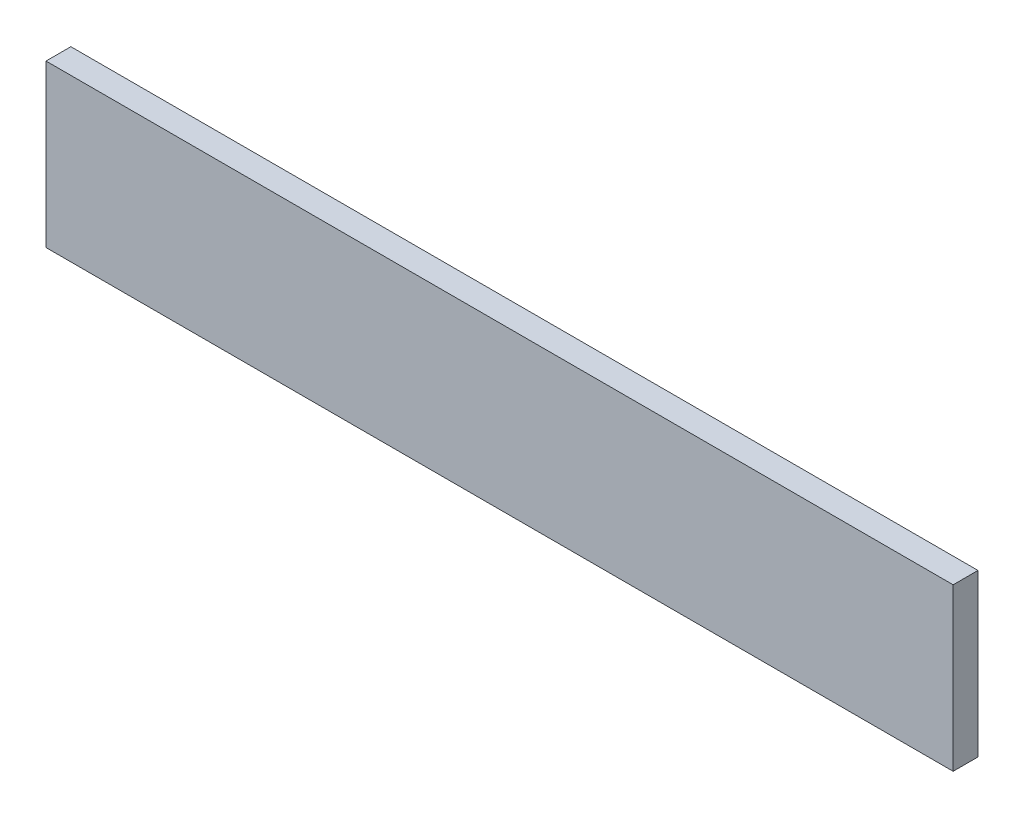
SolidWorks part; units mm, degrees
ref_plane "Front Plane" through (0, 0, 0) normal (0, 0, 1) x (1, 0, 0)
ref_plane "Top Plane" through (0, 0, 0) normal (0, 1, 0) x (1, 0, 0)
ref_plane "Right Plane" through (0, 0, 0) normal (1, 0, 0) x (0, 0, -1)
sketch "Sketch1" plane through (0, 0, 0) normal (0, 0, 1) x (1, 0, 0)
  line L0 (-115.8875, 0) -> (115.8875, 0) construction
  line L1 (-115.8875, 20.6375) -> (115.8875, 20.6375)
  line L2 (-115.8875, 20.6375) -> (-115.8875, -20.6375)
  line L3 (-115.8875, -20.6375) -> (115.8875, -20.6375)
  line L4 (115.8875, 20.6375) -> (115.8875, -20.6375)
  circle A0 centre (-95.25, 0) radius 7.1438
  circle A1 centre (-47.625, 0) radius 7.1438
  circle A2 centre (0, 0) radius 7.1438
  circle A3 centre (47.625, 0) radius 7.1437
  circle A4 centre (95.25, 0) radius 7.1438
  dimension "D1" = 14.2875
  dimension "D3" = 47.625
  dimension "D4" = 47.625
  dimension "D5" = 47.625
  dimension "D2" = 47.625
  dimension "B" = 231.775
  dimension "A" = 41.275
extrude "Boss-Extrude1" add sketch "Sketch1" along normal mid plane 6.35
sketch "Sketch2" plane through (0, 0, 3.175) normal (0, 0, 1) x (1, 0, 0)
  line L4 (-115.8875, 20.6375) -> (-115.8875, -20.6375)
  line L5 (-115.8875, -20.6375) -> (115.8875, -20.6375)
  line L6 (115.8875, -20.6375) -> (115.8875, 20.6375)
  line L7 (115.8875, 20.6375) -> (-115.8875, 20.6375)
  line L8 (-115.8875, 20.6375) -> (-115.8875, -20.6375)
  line L9 (-115.8875, -20.6375) -> (115.8875, -20.6375)
  line L10 (115.8875, -20.6375) -> (115.8875, 20.6375)
  line L11 (115.8875, 20.6375) -> (-115.8875, 20.6375)
  dimension "D1" = 0
extrude "Boss-Extrude2" add sketch "Sketch2" against normal up to surface (6.35 mm away) up to face at (54.7687, 0, -3.175)
